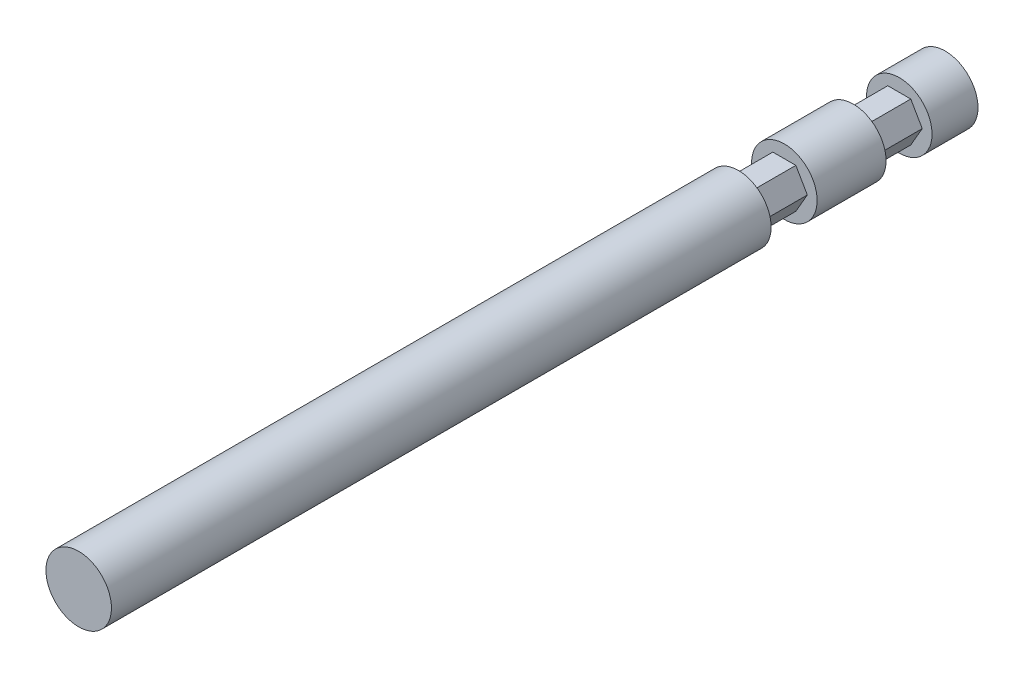
SolidWorks part; units mm, degrees
ref_plane "前视基准面" through (0, 0, 0) normal (0, 0, 1) x (1, 0, 0)
ref_plane "上视基准面" through (0, 0, 0) normal (0, 1, 0) x (1, 0, 0)
ref_plane "右视基准面" through (0, 0, 0) normal (1, 0, 0) x (0, 0, -1)
sketch "草图1" plane through (0, 0, 0) normal (0, 0, 1) x (1, 0, 0)
  circle A0 centre (0, 0) radius 2.85
  dimension "D1" = 5.7
extrude "凸台-拉伸1" add sketch "草图1" along normal blind 4
sketch "草图2" plane through (0, 0, 4) normal (0, 0, 1) x (1, 0, 0)
  line L1 (2, 0) -> (1, 1.7321)
  line L2 (1, 1.7321) -> (-1, 1.7321)
  line L3 (-1, 1.7321) -> (-2, 0)
  line L4 (-2, 0) -> (-1, -1.7321)
  line L5 (-1, -1.7321) -> (1, -1.7321)
  line L6 (1, -1.7321) -> (2, 0)
  circle A0 centre (0, 0) radius 2 construction
  dimension "D1" = 4
extrude "凸台-拉伸2" add sketch "草图2" along normal blind 4
sketch "草图3" plane through (0, 0, 8) normal (0, 0, 1) x (1, 0, 0)
  circle A1 centre (0, 0) radius 2.85
  point P7 (0, 0)
  dimension "D1" = 5.7
extrude "凸台-拉伸3" add sketch "草图3" along normal blind 6
sketch "草图4" plane through (0, 0, 14) normal (0, 0, 1) x (1, 0, 0)
  line L1 (2, 0) -> (1, 1.7321)
  line L2 (1, 1.7321) -> (-1, 1.7321)
  line L3 (-1, 1.7321) -> (-2, 0)
  line L4 (-2, 0) -> (-1, -1.7321)
  line L5 (-1, -1.7321) -> (1, -1.7321)
  line L6 (1, -1.7321) -> (2, 0)
  circle A0 centre (0, 0) radius 2 construction
  dimension "D1" = 4
extrude "凸台-拉伸4" add sketch "草图4" along normal blind 4
sketch "草图6" plane through (0, 0, 18) normal (0, 0, 1) x (1, 0, 0)
  circle A0 centre (0, 0) radius 2.85
  dimension "D1" = 5.7
extrude "凸台-拉伸5" add sketch "草图6" along normal blind 57.4
